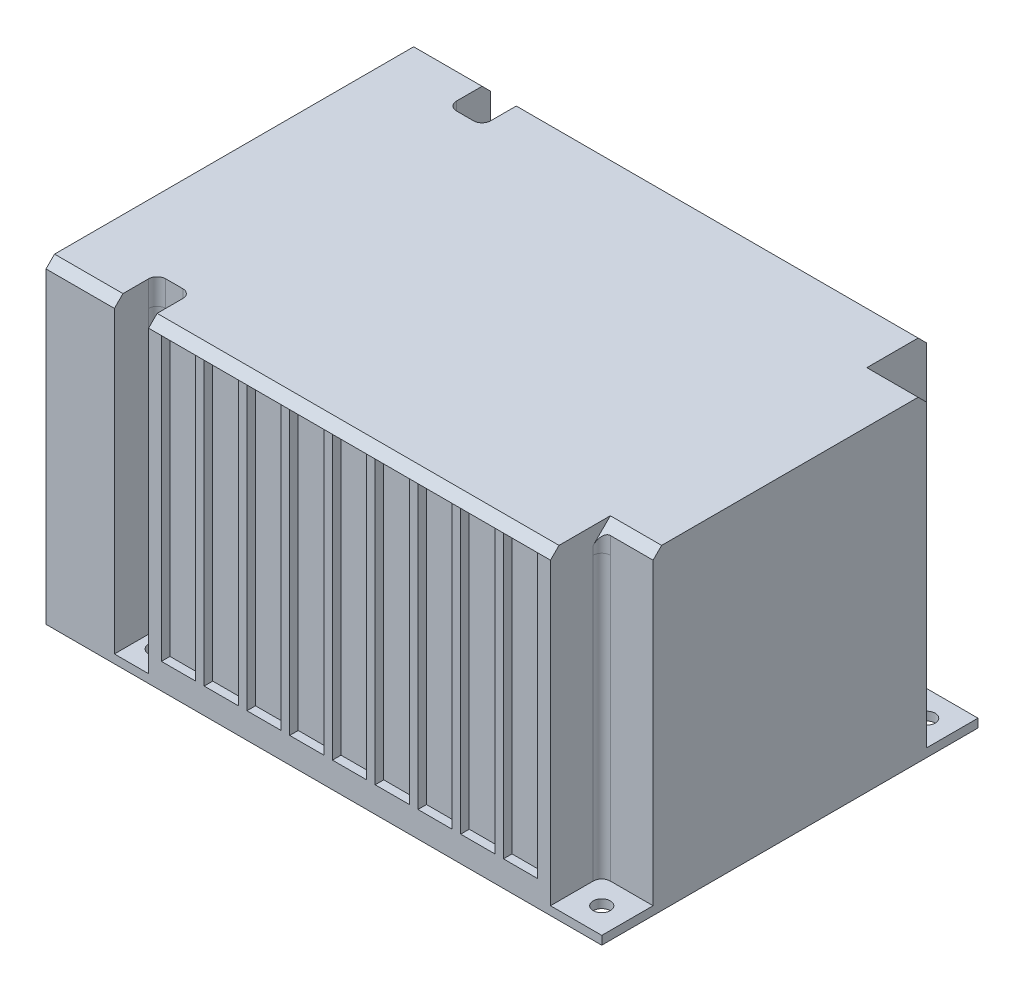
SolidWorks part; units mm, degrees
ref_plane "Спереди" through (0, 0, 0) normal (0, 0, 1) x (1, 0, 0)
ref_plane "Сверху" through (0, 0, 0) normal (0, 1, 0) x (1, 0, 0)
ref_plane "Справа" through (0, 0, 0) normal (1, 0, 0) x (0, 0, -1)
sketch "Sketch1" plane through (0, 0, 0) normal (0, 1, 0) x (1, 0, 0)
  line L2 (-43.2119, -60) -> (-63.2119, -60)
  line L3 (106.7881, 0) -> (106.7881, 60)
  line L4 (106.7881, 60) -> (-43.2119, 60)
  line L5 (-43.2119, -60) -> (106.7881, -60)
  line L6 (106.7881, -60) -> (106.7881, 0)
  line L7 (-63.2119, -60) -> (-63.2119, 60)
  line L8 (-63.2119, 60) -> (-43.2119, 60)
  line L9 (-63.2119, -60) -> (-63.2119, -52.5)
  line L10 (-63.2119, -52.5) -> (-55.7119, -52.5)
  line L12 (162.5, 80) -> (162.5, -80)
  line L14 (-122.5, 100) -> (-122.5, 110)
  line L15 (-162.5, 110) -> (-162.5, 100)
  line L16 (-112.5, 85) -> (-102.5, 85)
  line L17 (-112.5, 85) -> (-122.5, 85)
  line L18 (-122.5, 85) -> (-122.5, 100)
  line L20 (-102.5, 85) -> (-102.5, 100)
  line L22 (-132.5, 85) -> (-132.5, 95)
  line L23 (-132.5, 85) -> (-132.5, 75)
  line L24 (-132.5, 75) -> (-93.0036, 75)
  line L25 (-93.0036, 75) -> (-93.0036, 100)
  line L26 (-93.0036, 100) -> (122.5, 100)
  line L27 (152.5, 70) -> (122.5, 70)
  line L28 (132.5, 95) -> (132.5, 100)
  line L29 (147.5, 80) -> (152.5, 80)
  line L30 (132.5, 95) -> (132.5, 80)
  line L31 (132.5, 80) -> (147.5, 80)
  line L32 (-162.5, 110) -> (-122.5, 110)
  line L33 (-102.5, 100) -> (-102.5, 110)
  line L34 (-102.5, 110) -> (132.5, 110)
  line L35 (152.5, 80) -> (162.5, 80)
  line L36 (122.5, 70) -> (122.5, 100)
  line L37 (132.5, 100) -> (132.5, 110)
  line L38 (152.5, 70) -> (152.5, -70)
  line L39 (132.5, -100) -> (132.5, -110)
  line L40 (122.5, -70) -> (122.5, -100)
  line L41 (152.5, -80) -> (162.5, -80)
  line L42 (-102.5, -110) -> (132.5, -110)
  line L43 (-102.5, -100) -> (-102.5, -110)
  line L44 (-162.5, -110) -> (-122.5, -110)
  line L45 (132.5, -80) -> (147.5, -80)
  line L46 (132.5, -95) -> (132.5, -80)
  line L47 (147.5, -80) -> (152.5, -80)
  line L48 (132.5, -95) -> (132.5, -100)
  line L49 (152.5, -70) -> (122.5, -70)
  line L50 (-93.0036, -100) -> (122.5, -100)
  line L51 (-93.0036, -75) -> (-93.0036, -100)
  line L52 (-132.5, -75) -> (-93.0036, -75)
  line L53 (-132.5, -85) -> (-132.5, -75)
  line L54 (-132.5, -85) -> (-132.5, -95)
  line L55 (-102.5, -85) -> (-102.5, -100)
  line L57 (-122.5, -85) -> (-122.5, -100)
  line L58 (-112.5, -85) -> (-122.5, -85)
  line L59 (-112.5, -85) -> (-102.5, -85)
  line L60 (-162.5, -110) -> (-162.5, -100)
  line L61 (-122.5, -100) -> (-122.5, -110)
  line L62 (-162.5, 100) -> (-162.5, 95)
  line L63 (-162.5, 95) -> (-132.5, 95)
  line L64 (-162.5, -95) -> (-132.5, -95)
  line L65 (-162.5, -100) -> (-162.5, -95)
  circle A0 centre (147.5, -95) radius 5
  circle A2 centre (-112.5, -95) radius 5
  circle A6 centre (67.5, -105) radius 3
  circle A7 centre (-32.5, -105) radius 3
  circle A9 centre (157.5, -35) radius 3
  circle A10 centre (-55.7119, -52.5) radius 5
  circle A11 centre (99.2881, -52.5) radius 5
  circle A12 centre (99.2881, 52.5) radius 5
  circle A13 centre (-55.7119, 52.5) radius 5
  circle A14 centre (-112.5, 95) radius 5
  point P18 (162.5, 0)
  point P20 (152.5, 0)
extrude "Boss-Extrude1" add sketch "Sketch1" along normal blind 170 contours L51 L50 L40 L49 L38 L27 L36 L26 L25 L24 L23 L22 L63 L62 L15 L32 L14 L18 L17 L16 L20 L33 L34 L37 L28 L30 L31 L29 L35 L12 L41 L47 L45 L46 L48 L39 L42 L43 L55 L59 L58 L57 L61 L44 L60 L65 L64 L54 L53 L52
sketch "Sketch3" plane through (0, 0, 0) normal (0, 1, 0) x (1, 0, 0)
  line L0 (-122.5, -110) -> (-102.5, -110)
  line L1 (132.5, -110) -> (162.5, -110)
  line L2 (162.5, -110) -> (162.5, -80)
  line L3 (162.5, -80) -> (132.5, -80)
  line L4 (132.5, -80) -> (132.5, -110)
  line L5 (-122.5, -110) -> (-122.5, -85)
  line L6 (-122.5, -85) -> (-102.5, -85)
  line L7 (-102.5, -85) -> (-102.5, -110)
  line L8 (0, 0) -> (-187.8265, 0)
  line L9 (-102.5, 85) -> (-102.5, 110)
  line L10 (-122.5, 85) -> (-102.5, 85)
  line L11 (-122.5, 110) -> (-122.5, 85)
  line L12 (132.5, 80) -> (132.5, 110)
  line L13 (162.5, 80) -> (132.5, 80)
  line L14 (162.5, 110) -> (162.5, 80)
  line L15 (132.5, 110) -> (162.5, 110)
  line L16 (-122.5, 110) -> (-102.5, 110)
  line L17 (147.5, -80) -> (147.5, -95)
  circle A0 centre (-112.5, -95) radius 5
  circle A1 centre (147.5, -95) radius 5
  circle A2 centre (147.5, 95) radius 5
  circle A3 centre (-112.5, 95) radius 5
extrude "Boss-Extrude2" add sketch "Sketch3" along normal blind 5
fillet "Fillet1" radius 5 6 edges at (-122.5, 87.5, -85) (-102.5, 87.5, -85) (132.5, 87.5, -80) (132.5, 87.5, 80) (-102.5, 87.5, 85) (-122.5, 87.5, 85)
sketch "Sketch5" plane through (-132.5, 0, 0) normal (-1, 0, 0) x (0, 0, 1)
  circle A1 centre (-85, 25) radius 3
  circle A2 centre (85, 25) radius 3
  circle A4 centre (-85, 165) radius 3
  circle A5 centre (85, 165) radius 3
sketch "Sketch10" plane through (0, 170, 0) normal (0, 1, 0) x (1, 0, 0)
  line L7 (-162.5, 95) -> (-162.5, -95)
  line L9 (162.5, 80) -> (162.5, -80)
  line L10 (-122.5, 100) -> (-122.5, 110)
  line L11 (-162.5, 110) -> (-162.5, 100)
  line L12 (-112.5, 85) -> (-102.5, 85)
  line L13 (-112.5, 85) -> (-122.5, 85)
  line L14 (-122.5, 85) -> (-122.5, 100)
  line L15 (-102.5, 85) -> (-102.5, 100)
  line L16 (43.9708, 0) -> (-49956.0292, 0)
  line L23 (132.5, 95) -> (132.5, 100)
  line L24 (147.5, 80) -> (152.5, 80)
  line L25 (132.5, 95) -> (132.5, 80)
  line L26 (132.5, 80) -> (147.5, 80)
  line L27 (-162.5, 110) -> (-122.5, 110)
  line L28 (-102.5, 100) -> (-102.5, 110)
  line L29 (-102.5, 110) -> (132.5, 110)
  line L30 (152.5, 80) -> (162.5, 80)
  line L32 (132.5, 100) -> (132.5, 110)
  line L34 (132.5, -100) -> (132.5, -110)
  line L36 (152.5, -80) -> (162.5, -80)
  line L37 (-102.5, -110) -> (132.5, -110)
  line L38 (-102.5, -100) -> (-102.5, -110)
  line L39 (-162.5, -110) -> (-122.5, -110)
  line L40 (132.5, -80) -> (147.5, -80)
  line L41 (132.5, -95) -> (132.5, -80)
  line L42 (147.5, -80) -> (152.5, -80)
  line L43 (132.5, -95) -> (132.5, -100)
  line L50 (-102.5, -85) -> (-102.5, -100)
  line L51 (-122.5, -85) -> (-122.5, -100)
  line L52 (-112.5, -85) -> (-122.5, -85)
  line L53 (-112.5, -85) -> (-102.5, -85)
  line L54 (-162.5, -110) -> (-162.5, -100)
  line L55 (-122.5, -100) -> (-122.5, -110)
  line L56 (-162.5, 100) -> (-162.5, 95)
  line L59 (-162.5, -100) -> (-162.5, -95)
  circle A0 centre (147.5, -95) radius 5
  circle A1 centre (-112.5, -95) radius 5
  circle A2 centre (67.5, -105) radius 3
  circle A3 centre (-32.5, -105) radius 3
  circle A4 centre (157.5, -35) radius 3
  circle A9 centre (-112.5, 95) radius 5
  point P18 (162.5, 0)
  point P20 (152.5, 0)
extrude "Boss-Extrude5" add sketch "Sketch10" along normal blind 15 contours L7 L59 L54 L39 L55 L51 L52 L53 L50 L38 L37 L34 L43 L41 L40 L42 L36 L9 L30 L24 L26 L25 L23 L32 L29 L28 L15 L12 L13 L14 L10 L27 L11 L56
chamfer "Chamfer1" distance 5 angle 45 6 edges at (-142.5, 185, -110) (15, 185, -110) (147.5, 185, -80) (147.5, 185, 80) (15, 185, 110) (-142.5, 185, 110)
fillet "Fillet2" radius 5 6 edges at (-122.5, 177.5, -85) (-102.5, 177.5, -85) (132.5, 175, -80) (132.5, 175, 80) (-102.5, 177.5, 85) (-122.5, 177.5, 85)
sketch "Sketch15" plane through (0, 0, 0) normal (0, -1, 0) x (1, 0, 0)
  circle A2 centre (67.5, -105) radius 2
  circle A3 centre (-32.5, -105) radius 2
  circle A4 centre (157.5, -35) radius 2
  circle A10 centre (157.5, 35) radius 2
  circle A11 centre (67.5, 105) radius 2
  circle A12 centre (-32.5, 105) radius 2
sketch "Sketch16" plane through (-162.5, 0, 0) normal (-1, 0, 0) x (0, 0, 1)
  circle A0 centre (-102.5, 177.5) radius 3
  circle A1 centre (-102.5, 85) radius 3
  circle A8 centre (102.5, 177.5) radius 3
  circle A9 centre (102.5, 85) radius 3
  circle A10 centre (0, 177.5) radius 3
  dimension "D1" = 2
  dimension "D2" = 2
sketch "Sketch18" plane through (0, 0, 110) normal (0, 0, 1) x (1, 0, 0)
  line L2 (-162.5, 0) -> (162.5, 0) construction
  line L3 (-100, 0) -> (-95, 0)
  line L5 (132.5, 180) -> (-102.5, 180) construction
  line L7 (-75, 0) -> (-70, 0)
  line L11 (-50, 0) -> (-45, 0)
  line L12 (-45, 15) -> (-45, 180)
  line L15 (-25, 0) -> (-20, 0)
  line L16 (-20, 15) -> (-20, 180)
  line L19 (0, 0) -> (5, 0)
  line L20 (5, 15) -> (5, 180)
  line L23 (25, 0) -> (30, 0)
  line L24 (30, 15) -> (30, 180)
  line L25 (30, 180) -> (25, 180)
  line L27 (50, 0) -> (55, 0)
  line L28 (55, 15) -> (55, 180)
  line L31 (75, 0) -> (80, 0)
  line L32 (80, 15) -> (80, 180)
  line L35 (100, 0) -> (105, 0)
  line L38 (125, 180) -> (125, 15)
  line L39 (125, 0) -> (130, 0)
  line L42 (-70, 180) -> (-70, 15)
  line L44 (-95, 180) -> (-95, 15)
  line L45 (-95, 0) -> (-75, 0)
  line L46 (-75, 180) -> (-75, 15)
  line L48 (-50, 180) -> (-50, 15)
  line L49 (-70, 0) -> (-50, 0)
  line L50 (-45, 180) -> (-45, 15)
  line L51 (-45, 180) -> (-25, 180)
  line L52 (-25, 180) -> (-25, 15)
  line L53 (-45, 0) -> (-25, 0)
  line L54 (-20, 180) -> (-20, 15)
  line L55 (-20, 180) -> (0, 180)
  line L56 (0, 180) -> (0, 15)
  line L57 (-20, 0) -> (0, 0)
  line L58 (5, 180) -> (5, 15)
  line L59 (5, 180) -> (25, 180)
  line L60 (25, 180) -> (25, 15)
  line L61 (5, 0) -> (25, 0)
  line L62 (30, 180) -> (30, 15)
  line L63 (30, 180) -> (50, 180)
  line L64 (50, 180) -> (50, 15)
  line L65 (30, 0) -> (50, 0)
  line L66 (55, 180) -> (55, 15)
  line L67 (55, 180) -> (75, 180)
  line L68 (75, 180) -> (75, 15)
  line L69 (55, 0) -> (75, 0)
  line L70 (80, 180) -> (80, 15)
  line L71 (80, 180) -> (100, 180)
  line L72 (100, 180) -> (100, 15)
  line L73 (80, 0) -> (100, 0)
  line L74 (105, 180) -> (105, 15)
  line L75 (105, 180) -> (125, 180)
  line L76 (125, 180) -> (125, 15)
  line L77 (105, 0) -> (125, 0)
  line L78 (-95, 15) -> (-75, 15)
  line L79 (-20, 15) -> (0, 15)
  line L80 (-70, 15) -> (-50, 15)
  line L81 (-45, 15) -> (-25, 15)
  line L82 (5, 15) -> (25, 15)
  line L83 (30, 15) -> (50, 15)
  line L84 (55, 15) -> (75, 15)
  line L85 (80, 15) -> (100, 15)
  line L86 (105, 15) -> (125, 15)
  line L87 (-70, 180) -> (-50, 180)
  line L90 (-95, 180) -> (-75, 180)
  line M6 (132.5, 180) -> (-102.5, 180)
  dimension "D1" = 10
  dimension "D2" = 9
extrude "Cut-Extrude9" cut sketch "Sketch18" against normal blind 5 contours L12 L81 L52 M6 | L16 L79 L56 M6 | L20 L82 L60 M6 | L24 L83 L64 M6 | L28 L84 L68 M6 | L32 L85 L72 M6 | L74 L86 L38 M6 | L46 L78 L44 L90 | L42 L80 L48 L87
sketch "Sketch21" plane through (0, 0, -110) normal (0, 0, -1) x (-1, 0, 0)
  line L0 (-125, 15) -> (-105, 15)
  line L5 (-75, 15) -> (-75, 180)
  line L7 (-50, 15) -> (-50, 180)
  line L9 (-25, 15) -> (-25, 180)
  line L11 (0, 15) -> (0, 180)
  line L12 (0, 180) -> (-5, 180)
  line L14 (25, 15) -> (25, 180)
  line L16 (50, 15) -> (50, 180)
  line L18 (95, 180) -> (95, 15)
  line L20 (-100, 180) -> (-100, 15)
  line L21 (-125, 180) -> (-125, 15)
  line L23 (-105, 180) -> (-105, 15)
  line L24 (-80, 180) -> (-80, 15)
  line L26 (-75, 180) -> (-75, 15)
  line L27 (-75, 180) -> (-55, 180)
  line L28 (-55, 180) -> (-55, 15)
  line L30 (-50, 180) -> (-50, 15)
  line L31 (-50, 180) -> (-30, 180)
  line L32 (-30, 180) -> (-30, 15)
  line L34 (-25, 180) -> (-25, 15)
  line L35 (-25, 180) -> (-5, 180)
  line L36 (-5, 180) -> (-5, 15)
  line L38 (0, 180) -> (0, 15)
  line L39 (0, 180) -> (20, 180)
  line L40 (20, 180) -> (20, 15)
  line L42 (25, 180) -> (25, 15)
  line L43 (25, 180) -> (45, 180)
  line L44 (45, 180) -> (45, 15)
  line L46 (50, 180) -> (50, 15)
  line L47 (50, 180) -> (70, 180)
  line L48 (70, 180) -> (70, 15)
  line L50 (75, 180) -> (75, 15)
  line L51 (75, 180) -> (95, 180)
  line L52 (95, 180) -> (95, 15)
  line L55 (-50, 15) -> (-30, 15)
  line L56 (-100, 15) -> (-80, 15)
  line L57 (-75, 15) -> (-55, 15)
  line L58 (-25, 15) -> (-5, 15)
  line L59 (0, 15) -> (20, 15)
  line L60 (25, 15) -> (45, 15)
  line L61 (50, 15) -> (70, 15)
  line L62 (75, 15) -> (95, 15)
  line L63 (-100, 180) -> (-80, 180)
  line L64 (-125, 180) -> (-105, 180)
  line M30 (102.5, 180) -> (-132.5, 180)
extrude "Cut-Extrude10" cut sketch "Sketch21" against normal blind 5 contours L20 L56 L24 M30 | L5 L57 L28 M30 | L7 L55 L32 M30 | L9 L58 L36 M30 | L11 L59 L40 M30 | L14 L60 L44 M30 | L16 L61 L48 M30 | L50 L62 L18 M30 | L23 L0 L21 L64
hole_wizard "M4 Tapped Hole1" positions "Sketch24" profile "Sketch25" tap size "M4" standard "ISO"
sketch "Sketch24" plane through (0, 0, 0) normal (0, -1, 0) x (-1, 0, 0)
  point P0 (-157.5, 35)
  point P3 (-157.5, -35)
  point P6 (-67.5, -105)
  point P9 (32.5, -105)
  point P12 (32.5, 105)
  point P15 (-67.5, 105)
sketch "Sketch25" plane through (157.5, 0, -35) normal (1, 0, 0) x (0, 0, -1)
  line L0 (0, 0) -> (0, 5.9914)
  line L1 (0, 5.9914) -> (1.65, 5)
  line L2 (1.65, 5) -> (1.65, 0.375)
  line L3 (1.65, 0.375) -> (2.025, 0)
  line L5 (2.025, 0) -> (0, 0)
  line L6 (-1.65, 0.375) -> (-2.025, 0) construction
  line L10 (0, 5.9914) -> (-1.65, 5) construction
  line L11 (0, -6.35) -> (0, 107.95) construction
  dimension "Tap Drill Dia." = 3.3
  dimension "Tap Drill Depth" = 5
  dimension "Near C'Sink Dia." = 4.05
  dimension "Near C'Sink Angle" = 90
  dimension "Drill Angle" = 118
cosmetic thread "Hole Thread1" parameters "D1"=5, "D2"=4
cosmetic thread "Hole Thread2" parameters "D1"=5, "D2"=4
cosmetic thread "Hole Thread3" parameters "D1"=5, "D2"=4
cosmetic thread "Hole Thread4" parameters "D1"=5, "D2"=4
cosmetic thread "Hole Thread5" parameters "D1"=5, "D2"=4
cosmetic thread "Hole Thread6" parameters "D1"=5, "D2"=4
hole_wizard "M6 Tapped Hole1" positions "Sketch28" profile "Sketch27" tap size "M6" standard "ISO"
sketch "Sketch28" plane through (-132.5, 0, 0) normal (-1, 0, 0) x (0, 0, 1)
  point P0 (-85, 25)
  point P3 (-85, 165)
  point P6 (85, 165)
  point P9 (85, 25)
sketch "Sketch27" plane through (-132.5, 25, -85) normal (0, 1, 0) x (0, 0, 1)
  line L0 (0, 0) -> (0, 6.5022)
  line L1 (0, 6.5022) -> (2.5, 5)
  line L2 (2.5, 5) -> (2.5, 0.525)
  line L3 (2.5, 0.525) -> (3.025, 0)
  line L5 (3.025, 0) -> (0, 0)
  line L6 (-2.5, 0.525) -> (-3.025, 0) construction
  line L10 (0, 6.5022) -> (-2.5, 5) construction
  line L11 (0, -6.35) -> (0, 107.95) construction
  dimension "Tap Drill Dia." = 5
  dimension "Tap Drill Depth" = 5
  dimension "Near C'Sink Dia." = 6.05
  dimension "Near C'Sink Angle" = 90
  dimension "Drill Angle" = 118
cosmetic thread "Hole Thread7" parameters "D1"=5, "D2"=6
cosmetic thread "Hole Thread8" parameters "D1"=5, "D2"=6
cosmetic thread "Hole Thread9" parameters "D1"=5, "D2"=6
cosmetic thread "Hole Thread10" parameters "D1"=5, "D2"=6
hole_wizard "M6 Tapped Hole2" positions "Sketch29" profile "Sketch30" tap size "M6" standard "ISO"
sketch "Sketch29" plane through (-162.5, 0, 0) normal (-1, 0, 0) x (0, 0, 1)
  point P0 (-102.5, 85)
  point P3 (-102.5, 177.5)
  point P6 (0, 177.5)
  point P9 (102.5, 177.5)
  point P12 (102.5, 85)
sketch "Sketch30" plane through (-162.5, 85, -102.5) normal (0, 1, 0) x (0, 0, 1)
  line L0 (0, 0) -> (0, 6.5022)
  line L1 (0, 6.5022) -> (2.5, 5)
  line L2 (2.5, 5) -> (2.5, 0)
  line L5 (2.5, 0) -> (0, 0)
  line L10 (0, 6.5022) -> (-2.5, 5) construction
  line L11 (0, -6.35) -> (0, 107.95) construction
  dimension "Tap Drill Dia." = 5
  dimension "Tap Drill Depth" = 5
  dimension "Drill Angle" = 118
cosmetic thread "Hole Thread11" parameters "D1"=5, "D2"=6
cosmetic thread "Hole Thread12" parameters "D1"=5, "D2"=6
cosmetic thread "Hole Thread13" parameters "D1"=5, "D2"=6
cosmetic thread "Hole Thread14" parameters "D1"=5, "D2"=6
cosmetic thread "Hole Thread15" parameters "D1"=5, "D2"=6
sketch "Sketch31" plane through (0, 5, 0) normal (0, 1, 0) x (1, 0, 0)
  circle A0 centre (147.5, 95) radius 5
  circle A1 centre (-112.5, 95) radius 5
  circle A2 centre (-112.5, -95) radius 5
  circle A3 centre (147.5, -95) radius 5
  dimension "D1" = 2
  dimension "D2" = 2
extrude "Cut-Extrude11" cut sketch "Sketch31" against normal through all
